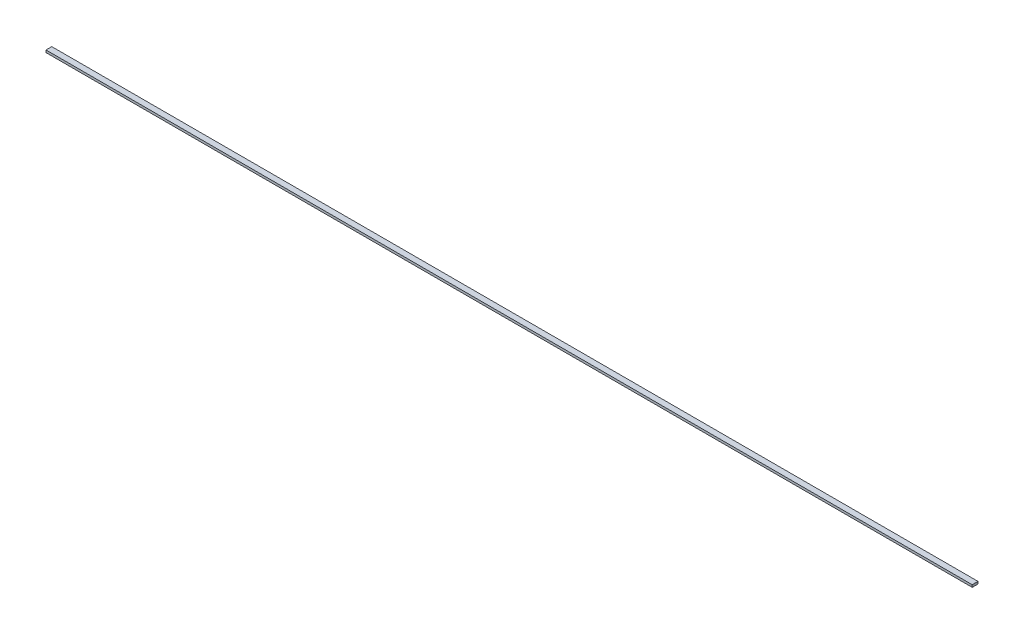
SolidWorks part; units mm, degrees
ref_plane "Front Plane" through (0, 0, 0) normal (0, 0, 1) x (1, 0, 0)
ref_plane "Top Plane" through (0, 0, 0) normal (0, 1, 0) x (1, 0, 0)
ref_plane "Right Plane" through (0, 0, 0) normal (1, 0, 0) x (0, 0, -1)
sketch "Sketch1" plane through (0, 0, 0) normal (0, 0, 1) x (1, 0, 0)
  line L1 (200.1, -0.5) -> (-200.1, -0.5)
  line L2 (200.1, -0.5) -> (200.1, 0.5)
  line L3 (200.1, 0.5) -> (-200.1, 0.5)
  line L4 (-200.1, -0.5) -> (-200.1, 0.5)
  line L5 (200.1, -0.5) -> (-200.1, 0.5) construction
  line L6 (200.1, 0.5) -> (-200.1, -0.5) construction
  point P0 (0, 0)
  dimension "D1" = 1
  dimension "D2" = 400.2
extrude "Boss-Extrude1" add sketch "Sketch1" along normal blind 2.5
